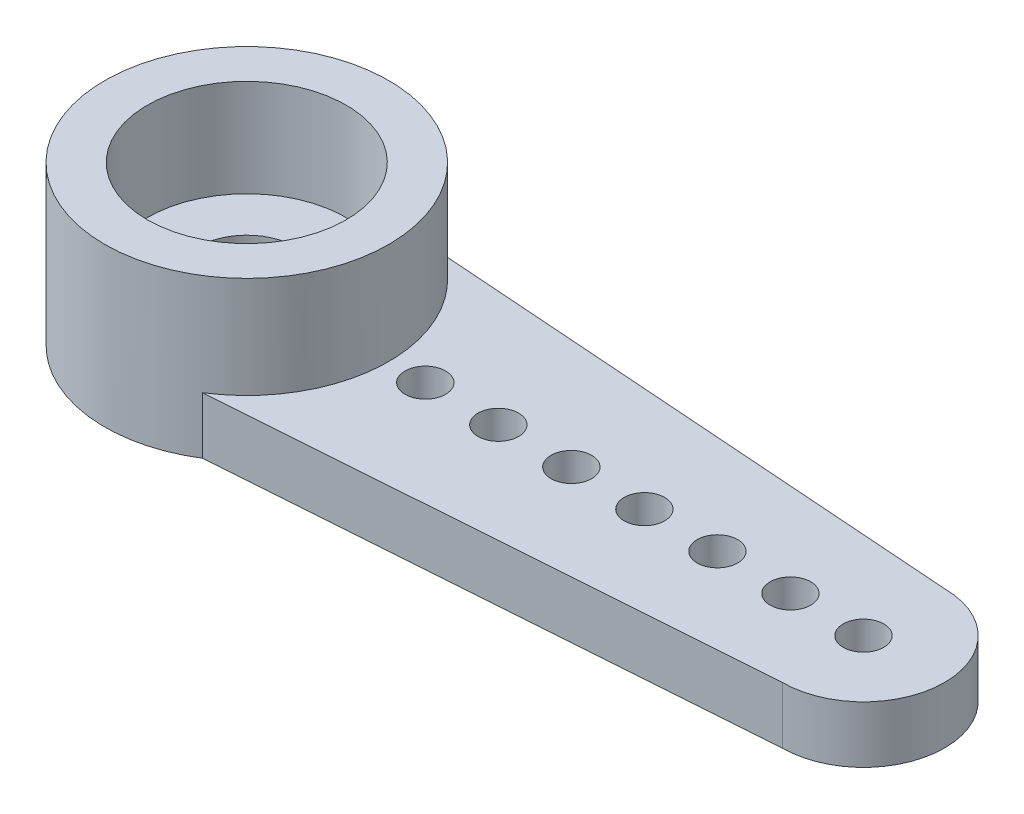
SolidWorks part; units mm, degrees
other "Camera1"
material "ABS"
ref_plane "Front Plane" through (0, 0, 0) normal (0, 0, 1) x (1, 0, 0)
ref_plane "Top Plane" through (0, 0, 0) normal (0, 1, 0) x (1, 0, 0)
ref_plane "Right Plane" through (0, 0, 0) normal (1, 0, 0) x (0, 0, -1)
sketch "Sketch1" plane through (0, 0, 0) normal (0, 1, 0) x (1, 0, 0)
  line L0 (-17.2, 0) -> (17.2, 0) construction
  line L1 (0, -8.35) -> (0, 8.35) construction
  line L2 (-15.2, 2) -> (-2, 2.95)
  line L3 (-15.2, -2) -> (-2, -2.95)
  line L4 (2, 6.35) -> (2, 3.5)
  line L5 (-2, 6.35) -> (-2, 2.95)
  line L6 (2, -6.35) -> (2, -3.5)
  line L7 (-2, -6.35) -> (-2, -2.95)
  line L8 (15.2, 2) -> (2, 3.5)
  line L9 (15.2, -2) -> (2, -3.5)
  circle A0 centre (0, 0) radius 3.5 construction
  arc A1 (-15.2, 2) -> (-15.2, -2) centre (-15.2, 0) ccw
  arc A2 (15.2, 2) -> (15.2, -2) centre (15.2, 0) cw
  arc A3 (2, 6.35) -> (-2, 6.35) centre (0, 6.35) ccw
  circle A4 centre (0, 6.35) radius 0.5
  circle A5 centre (0, 4.55) radius 0.5
  circle A6 centre (0, -4.55) radius 0.5
  circle A7 centre (0, -6.35) radius 0.5
  arc A8 (2, -6.35) -> (-2, -6.35) centre (0, -6.35) cw
  circle A10 centre (-15.2, 0) radius 0.5
  circle A11 centre (15.2, 0) radius 0.5
  circle A12 centre (-13.4, 0) radius 0.5
  circle A13 centre (-11.6, 0) radius 0.5
  circle A14 centre (-9.8, 0) radius 0.5
  circle A15 centre (-8, 0) radius 0.5
  circle A16 centre (-6.2, 0) radius 0.5
  circle A17 centre (-4.4, 0) radius 0.5
  circle A18 centre (13.4, 0) radius 0.5
  circle A19 centre (11.6, 0) radius 0.5
  circle A20 centre (9.8, 0) radius 0.5
  circle A21 centre (8, 0) radius 0.5
  circle A22 centre (6.2, 0) radius 0.5
  circle A23 centre (4.4, 0) radius 0.5
  point P5 (0, 0)
  point P8 (0, 0)
  point P25 (0, 6.85)
  point P26 (0, 4.05)
  dimension "D1" = 7
  dimension "D4" = 4
  dimension "D6" = 1
  dimension "D2" = 34.4
  dimension "D3" = 16.7
  dimension "D5" = 2
  dimension "D7" = 2.8
  dimension "D8" = 7
  dimension "D10" = 5.9
  dimension "D11" = 7
  dimension "D12" = 7
extrude "Boss-Extrude1" add sketch "Sketch1" along normal blind 1.4
sketch "Sketch2" plane through (0, 0, 0) normal (0, -1, 0) x (1, 0, 0)
  circle A0 centre (0, 0) radius 2.35
  dimension "D1" = 4.7
extrude "Cut-Extrude1" cut sketch "Sketch2" against normal blind 1
sketch "Sketch3" plane through (0, 1.4, 0) normal (0, 1, 0) x (1, 0, 0)
  circle A0 centre (0, 0) radius 2.45
  circle A1 centre (0, 0) radius 3.5
  dimension "D1" = 4.9
  dimension "D2" = 7
extrude "Boss-Extrude2" add sketch "Sketch3" along normal blind 2.5
sketch "Sketch4" plane through (0, 1.4, 0) normal (0, 1, 0) x (1, 0, 0)
  circle A0 centre (0, 0) radius 1.2
  dimension "D1" = 2.4
extrude "Cut-Extrude2" cut sketch "Sketch4" against normal through all
sketch "Sketch5" plane through (0, 1.4, 0) normal (0, 1, 0) x (1, 0, 0)
  circle A0 centre (0, 0) radius 1.2 construction
  circle A1 centre (0, 0) radius 2.45
  circle A2 centre (0, 0) radius 2.45
  circle A3 centre (0, 0) radius 1.2
  dimension "D1" = 0
extrude "Boss-Extrude3" add sketch "Sketch5" along normal blind 0.1
sketch "Sketch6" plane through (0, 0, 0) normal (0, -1, 0) x (1, 0, 0)
  line L0 (-2, -2.95) -> (-15.2, -2) construction
  line L1 (-1.8686, -2.9595) -> (-15.2, -2)
  line L2 (-15.2, 2) -> (-2, 2.95) construction
  line L3 (-15.2, 2) -> (-1.8686, 2.9595)
  line L4 (0, -9.3016) -> (0, 8.6978) construction
  line L5 (1.8686, -2.9595) -> (15.2, -2)
  line L6 (15.2, 2) -> (1.8686, 2.9595)
  line L8 (-17.8676, -8.836) -> (17.8676, -8.836)
  line L9 (-17.8676, -8.836) -> (-17.8676, 8.836)
  line L10 (-17.8676, 8.836) -> (17.8676, 8.836)
  line L11 (17.8676, -8.836) -> (17.8676, 8.836)
  line L12 (-17.8676, -8.836) -> (17.8676, 8.836) construction
  line L13 (-17.8676, 8.836) -> (17.8676, -8.836) construction
  arc A0 (-15.2, 2) -> (-15.2, -2) centre (-15.2, 0) ccw construction
  arc A1 (-15.2, 2) -> (-15.2, -2) centre (-15.2, 0) ccw
  circle A2 centre (0, 0) radius 3.5 construction
  arc A3 (1.8686, 2.9595) -> (-1.8686, 2.9595) centre (0, 0) ccw
  arc A4 (15.2, 2) -> (15.2, -2) centre (15.2, 0) cw
  arc A5 (-1.8686, -2.9595) -> (1.8686, -2.9595) centre (0, 0) ccw
extrude "Cut-Extrude4" cut sketch "Sketch6" against normal through all
sketch "Sketch7" plane through (0, 0, 0) normal (0, -1, 0) x (1, 0, 0)
  line L0 (0, 3.5) -> (-17.7318, 3.5)
  line L1 (-17.7318, 3.5) -> (-17.7318, -3.5)
  line L2 (-17.7318, -3.5) -> (0, -3.5)
  circle A0 centre (0, 0) radius 3.5 construction
  arc A1 (0, 3.5) -> (0, -3.5) centre (0, 0) ccw
extrude "Cut-Extrude5" cut sketch "Sketch7" against normal through all
sketch "Sketch8" plane through (0, 3.9, 0) normal (0, 1, 0) x (1, 0, 0)
  circle A0 centre (0, 0) radius 3.5 construction
  arc A1 (15.2, -2) -> (15.2, 2) centre (15.2, 0) ccw construction
  point P0 (-3.5, 0)
  point P1 (17.2, 0)
  dimension "D1" = 20.7
scale "Scale1" bodies to scale 107 scale about centroid uniform scaling yes scale factor 0.5
scale "Scale2" bodies to scale 108 scale about centroid uniform scaling yes scale factor 2.5
